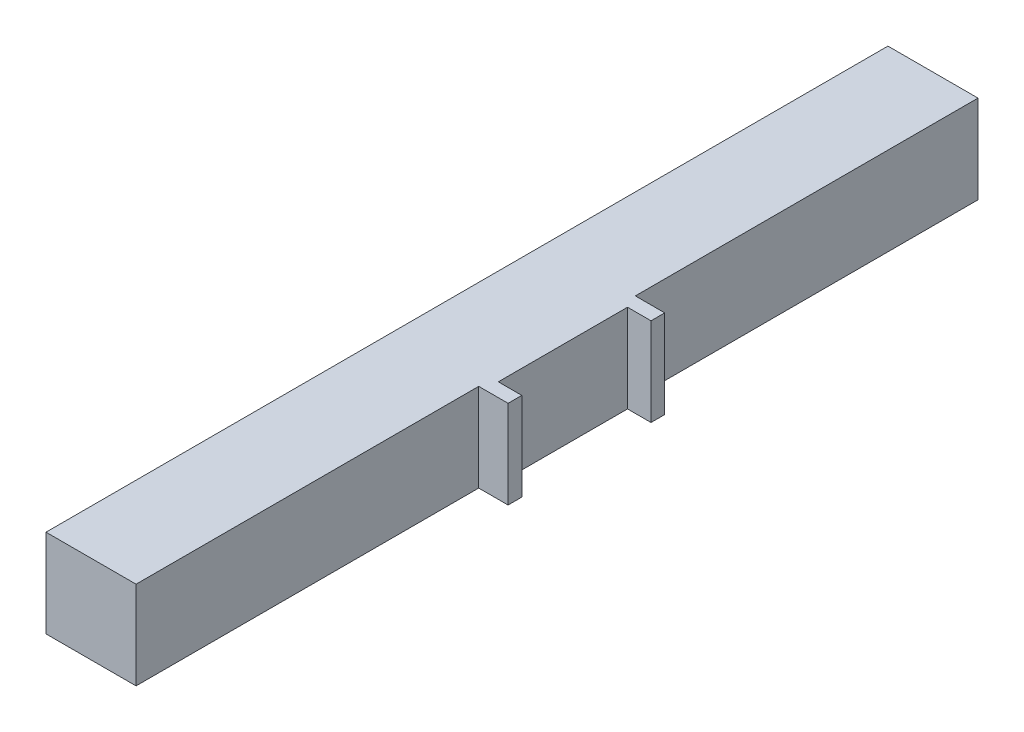
SolidWorks part; units mm, degrees
ref_plane "Front Plane" through (0, 0, 0) normal (0, 0, 1) x (1, 0, 0)
ref_plane "Top Plane" through (0, 0, 0) normal (0, 1, 0) x (1, 0, 0)
ref_plane "Right Plane" through (0, 0, 0) normal (1, 0, 0) x (0, 0, -1)
sketch "Sketch1" plane through (0, 0, 0) normal (0, 0, 1) x (1, 0, 0)
  line L1 (-23, 22.5) -> (23, 22.5)
  line L2 (-23, 22.5) -> (-23, -22.5)
  line L3 (-23, -22.5) -> (23, -22.5)
  line L4 (23, 22.5) -> (23, -22.5)
  line L5 (-23, 22.5) -> (23, -22.5) construction
  line L6 (-23, -22.5) -> (23, 22.5) construction
  point P0 (0, 0)
  dimension "D1" = 46
  dimension "D2" = 45
extrude "Boss-Extrude1" add sketch "Sketch1" along normal blind 430
sketch "Sketch2" plane through (23, 0, 0) normal (1, 0, 0) x (0, 0, -1)
  line L0 (-430, 22.5) -> (0, 22.5)
  line L1 (0, 22.5) -> (0, -22.5)
  line L2 (0, -22.5) -> (-430, -22.5)
  line L3 (-430, -22.5) -> (-430, 22.5)
  line L4 (-255, 22.5) -> (-255, -22.5)
  line L5 (-175, 22.5) -> (-175, -22.5)
  line L6 (-215, 22.5) -> (-215, -22.5) construction
  line M5 (0, 22.5) -> (-430, 22.5)
  line M7 (-430, -22.5) -> (0, -22.5)
  dimension "D1" = 80
  dimension "D2" = 40
  dimension "D3" = 215
extrude "Boss-Extrude2" add sketch "Sketch2" along normal blind 15 contours L0 L6 L5 M7 | L6 L4 L2 M5
sketch "Sketch3" plane through (0, 22.5, 0) normal (0, 1, 0) x (1, 0, 0)
  line L0 (23, -175) -> (23, -255)
  line L1 (23, -255) -> (38, -255)
  line L2 (38, -255) -> (38, -175)
  line L3 (38, -175) -> (23, -175)
  line L4 (38, -182) -> (26, -182)
  line L5 (26, -182) -> (26, -248)
  line L6 (26, -248) -> (38, -248)
  dimension "D1" = 7
  dimension "D2" = 7
  dimension "D3" = 3
extrude "Cut-Extrude2" cut sketch "Sketch3" against normal blind 3434 contours L5 L6 L2 L4
sketch "Sketch4" plane through (26, 0, 0) normal (1, 0, 0) x (0, 0, -1)
  line L0 (-215, -22.5) -> (-215, 61.9155) construction
  line L1 (-182, -22.5) -> (-248, -22.5) construction
  line L2 (-255, 22.5) -> (-255, -22.5) construction
  dimension "D1" = 40
ref_plane "Plane1" through (0, 0, 215) normal (0, 0, 1) x (1, 0, 0)
sketch "Sketch5" plane through (0, 0, 215) normal (0, 0, 1) x (1, 0, 0)
  line L0 (-23, 22.5) -> (-23, -22.5) construction
  line L1 (38, 22.5) -> (23, 22.5) construction
  circle A0 centre (26.1107, -22.5334) radius 5
  circle A1 centre (26, 22.5) radius 5
  dimension "D1" = 10
  dimension "D4" = 10
  dimension "D2" = 49.1107
  dimension "D3" = 45.0334
